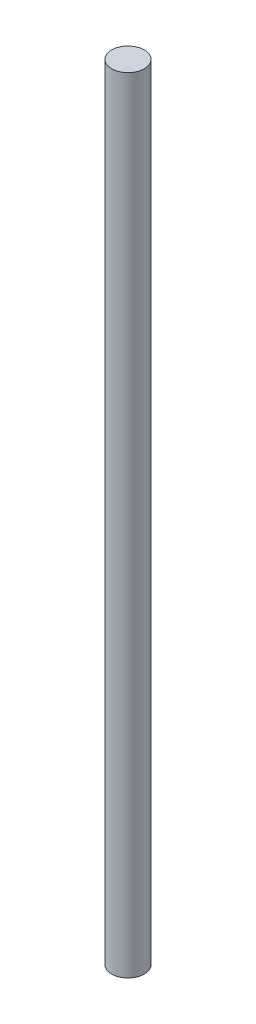
SolidWorks part; units mm, degrees
ref_plane "Front Plane" through (0, 0, 0) normal (0, 0, 1) x (1, 0, 0)
ref_plane "Top Plane" through (0, 0, 0) normal (0, 1, 0) x (1, 0, 0)
ref_plane "Right Plane" through (0, 0, 0) normal (1, 0, 0) x (0, 0, -1)
sketch "Sketch1" plane through (0, 0, 0) normal (0, 1, 0) x (1, 0, 0)
  circle A0 centre (0, 0) radius 1.5
  dimension "D1" = 3
extrude "Boss-Extrude1" add sketch "Sketch1" along normal blind 72
